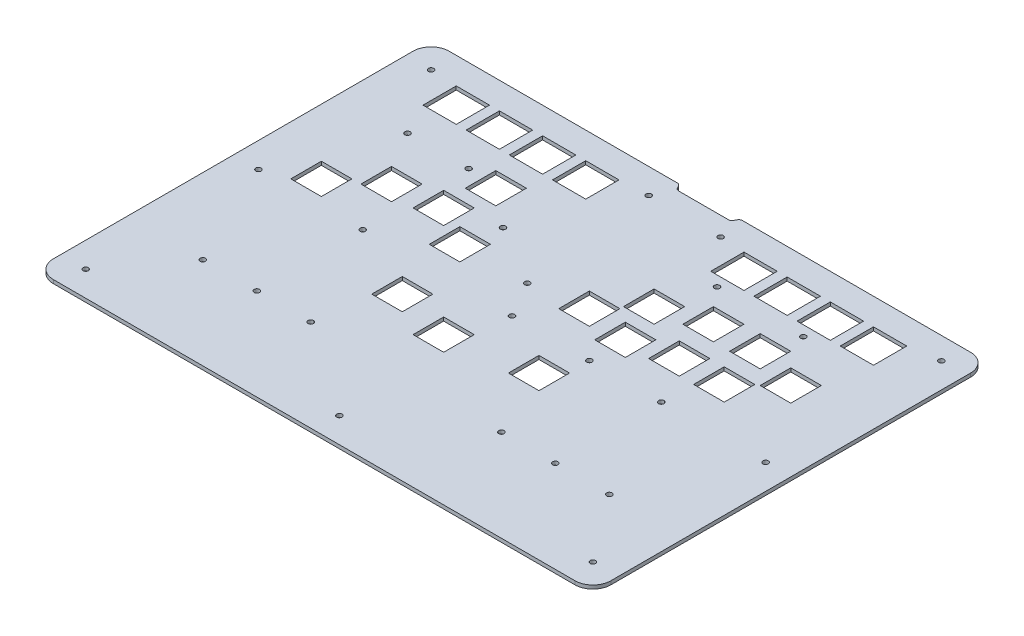
SolidWorks part; units mm, degrees
ref_plane "前视基准面" through (0, 0, 0) normal (0, 0, 1) x (1, 0, 0)
ref_plane "上视基准面" through (0, 0, 0) normal (0, 1, 0) x (1, 0, 0)
ref_plane "右视基准面" through (0, 0, 0) normal (1, 0, 0) x (0, 0, -1)
sketch "草图1" plane through (0, 0, 0) normal (0, 1, 0) x (1, 0, 0)
  line L0 (183.25, -128.5) -> (183.25, -131.5) construction
  line L1 (10, 0) -> (136.8844, 0)
  line L2 (0, -10) -> (0, -210)
  line L3 (10, -220) -> (300, -220)
  line L4 (310, -10) -> (310, -210)
  line L5 (28.75, -14.75) -> (47.25, -14.75)
  line L6 (28.75, -14.75) -> (28.75, -33.25)
  line L7 (28.75, -33.25) -> (47.25, -33.25)
  line L8 (173, -85) -> (173, 0) construction
  line L9 (173, -85) -> (310, -85) construction
  line L10 (190, -66) -> (190, 0) construction
  line L11 (215, -58) -> (215, 0) construction
  line L12 (241, -58) -> (241, 0) construction
  line L13 (247, -84) -> (247, 0) construction
  line L14 (222, -84) -> (222, 0) construction
  line L15 (0, -220) -> (310, 0) construction
  line L16 (241, -58) -> (310, -58) construction
  line L17 (247, -84) -> (310, -84) construction
  line L18 (215, -58) -> (310, -58) construction
  line L19 (222, -84) -> (310, -84) construction
  line L20 (190, -66) -> (310, -66) construction
  line L21 (310, -220) -> (0, 0) construction
  line L22 (141.1791, -3.5) -> (143.5, -3.5)
  line L23 (139.4291, -2.4682) -> (138.6344, -1.0318)
  line L24 (170.5709, -2.4682) -> (171.3656, -1.0318)
  line L25 (173.1156, 0) -> (300, 0)
  line L26 (155, -110) -> (155, -220) construction
  line L27 (47.25, -14.75) -> (47.25, -33.25)
  line L28 (28.75, -14.75) -> (47.25, -33.25) construction
  line L29 (28.75, -33.25) -> (47.25, -14.75) construction
  line L30 (52.75, -14.75) -> (71.25, -14.75)
  line L31 (52.75, -14.75) -> (52.75, -33.25)
  line L32 (52.75, -33.25) -> (71.25, -33.25)
  line L33 (71.25, -14.75) -> (71.25, -33.25)
  line L34 (52.75, -14.75) -> (71.25, -33.25) construction
  line L35 (52.75, -33.25) -> (71.25, -14.75) construction
  line L36 (76.75, -14.75) -> (95.25, -14.75)
  line L37 (76.75, -14.75) -> (76.75, -33.25)
  line L38 (76.75, -33.25) -> (95.25, -33.25)
  line L39 (95.25, -14.75) -> (95.25, -33.25)
  line L40 (76.75, -14.75) -> (95.25, -33.25) construction
  line L41 (76.75, -33.25) -> (95.25, -14.75) construction
  line L42 (100.75, -14.75) -> (119.25, -14.75)
  line L43 (100.75, -14.75) -> (100.75, -33.25)
  line L44 (100.75, -33.25) -> (119.25, -33.25)
  line L45 (119.25, -14.75) -> (119.25, -33.25)
  line L46 (100.75, -14.75) -> (119.25, -33.25) construction
  line L47 (100.75, -33.25) -> (119.25, -14.75) construction
  line L48 (188.75, -14.75) -> (207.25, -14.75)
  line L49 (188.75, -14.75) -> (188.75, -33.25)
  line L50 (188.75, -33.25) -> (207.25, -33.25)
  line L51 (207.25, -14.75) -> (207.25, -33.25)
  line L52 (188.75, -14.75) -> (207.25, -33.25) construction
  line L53 (188.75, -33.25) -> (207.25, -14.75) construction
  line L54 (212.75, -14.75) -> (231.25, -14.75)
  line L55 (212.75, -14.75) -> (212.75, -33.25)
  line L56 (212.75, -33.25) -> (231.25, -33.25)
  line L57 (231.25, -14.75) -> (231.25, -33.25)
  line L58 (212.75, -14.75) -> (231.25, -33.25) construction
  line L59 (212.75, -33.25) -> (231.25, -14.75) construction
  line L60 (236.75, -14.75) -> (255.25, -14.75)
  line L61 (236.75, -14.75) -> (236.75, -33.25)
  line L62 (236.75, -33.25) -> (255.25, -33.25)
  line L63 (255.25, -14.75) -> (255.25, -33.25)
  line L64 (236.75, -14.75) -> (255.25, -33.25) construction
  line L65 (236.75, -33.25) -> (255.25, -14.75) construction
  line L66 (260.75, -14.75) -> (279.25, -14.75)
  line L67 (260.75, -14.75) -> (260.75, -33.25)
  line L68 (260.75, -33.25) -> (279.25, -33.25)
  line L69 (279.25, -14.75) -> (279.25, -33.25)
  line L70 (260.75, -14.75) -> (279.25, -33.25) construction
  line L71 (260.75, -33.25) -> (279.25, -14.75) construction
  line L72 (183, -123) -> (197, -123) construction
  line L73 (183, -123) -> (183, -128.25) construction
  line L74 (183, -137) -> (197, -137) construction
  line L75 (197, -123) -> (197, -128.25) construction
  line L76 (183, -123) -> (197, -137) construction
  line L77 (183, -137) -> (197, -123) construction
  line L78 (183.25, -128.5) -> (183, -128.25) construction
  line L79 (183.25, -131.5) -> (183, -131.75) construction
  line L80 (196.75, -128.5) -> (196.75, -131.5) construction
  line L81 (196.75, -128.5) -> (197, -128.25) construction
  line L82 (196.75, -131.5) -> (197, -131.75) construction
  line L83 (183, -131.75) -> (183, -137) construction
  line L84 (197, -131.75) -> (197, -137) construction
  line L85 (31.25, -22.5) -> (31.25, -25.5) construction
  line L86 (31, -17) -> (45, -17) construction
  line L87 (31, -17) -> (31, -22.25) construction
  line L88 (31, -31) -> (45, -31) construction
  line L89 (45, -17) -> (45, -22.25) construction
  line L90 (31, -17) -> (45, -31) construction
  line L91 (31, -31) -> (45, -17) construction
  line L92 (31.25, -22.5) -> (31, -22.25) construction
  line L93 (31.25, -25.5) -> (31, -25.75) construction
  line L94 (44.75, -22.5) -> (44.75, -25.5) construction
  line L95 (44.75, -22.5) -> (45, -22.25) construction
  line L96 (44.75, -25.5) -> (45, -25.75) construction
  line L97 (31, -25.75) -> (31, -31) construction
  line L98 (45, -25.75) -> (45, -31) construction
  line L99 (55.25, -22.5) -> (55.25, -25.5) construction
  line L100 (55, -17) -> (69, -17) construction
  line L101 (55, -17) -> (55, -22.25) construction
  line L102 (55, -31) -> (69, -31) construction
  line L103 (69, -17) -> (69, -22.25) construction
  line L104 (55, -17) -> (69, -31) construction
  line L105 (55, -31) -> (69, -17) construction
  line L106 (55.25, -22.5) -> (55, -22.25) construction
  line L107 (55.25, -25.5) -> (55, -25.75) construction
  line L108 (68.75, -22.5) -> (68.75, -25.5) construction
  line L109 (68.75, -22.5) -> (69, -22.25) construction
  line L110 (68.75, -25.5) -> (69, -25.75) construction
  line L111 (55, -25.75) -> (55, -31) construction
  line L112 (69, -25.75) -> (69, -31) construction
  line L113 (79.25, -22.5) -> (79.25, -25.5) construction
  line L114 (79, -17) -> (93, -17) construction
  line L115 (79, -17) -> (79, -22.25) construction
  line L116 (79, -31) -> (93, -31) construction
  line L117 (93, -17) -> (93, -22.25) construction
  line L118 (79, -17) -> (93, -31) construction
  line L119 (79, -31) -> (93, -17) construction
  line L120 (79.25, -22.5) -> (79, -22.25) construction
  line L121 (79.25, -25.5) -> (79, -25.75) construction
  line L122 (92.75, -22.5) -> (92.75, -25.5) construction
  line L123 (92.75, -22.5) -> (93, -22.25) construction
  line L124 (92.75, -25.5) -> (93, -25.75) construction
  line L125 (79, -25.75) -> (79, -31) construction
  line L126 (93, -25.75) -> (93, -31) construction
  line L127 (103.25, -22.5) -> (103.25, -25.5) construction
  line L128 (103, -17) -> (117, -17) construction
  line L129 (103, -17) -> (103, -22.25) construction
  line L130 (103, -31) -> (117, -31) construction
  line L131 (117, -17) -> (117, -22.25) construction
  line L132 (103, -17) -> (117, -31) construction
  line L133 (103, -31) -> (117, -17) construction
  line L134 (103.25, -22.5) -> (103, -22.25) construction
  line L135 (103.25, -25.5) -> (103, -25.75) construction
  line L136 (116.75, -22.5) -> (116.75, -25.5) construction
  line L137 (116.75, -22.5) -> (117, -22.25) construction
  line L138 (116.75, -25.5) -> (117, -25.75) construction
  line L139 (103, -25.75) -> (103, -31) construction
  line L140 (117, -25.75) -> (117, -31) construction
  line L141 (191.25, -22.5) -> (191.25, -25.5) construction
  line L142 (191, -17) -> (205, -17) construction
  line L143 (191, -17) -> (191, -22.25) construction
  line L144 (191, -31) -> (205, -31) construction
  line L145 (205, -17) -> (205, -22.25) construction
  line L146 (191, -17) -> (205, -31) construction
  line L147 (191, -31) -> (205, -17) construction
  line L148 (191.25, -22.5) -> (191, -22.25) construction
  line L149 (191.25, -25.5) -> (191, -25.75) construction
  line L150 (204.75, -22.5) -> (204.75, -25.5) construction
  line L151 (204.75, -22.5) -> (205, -22.25) construction
  line L152 (204.75, -25.5) -> (205, -25.75) construction
  line L153 (191, -25.75) -> (191, -31) construction
  line L154 (205, -25.75) -> (205, -31) construction
  line L155 (215.25, -22.5) -> (215.25, -25.5) construction
  line L156 (215, -17) -> (229, -17) construction
  line L157 (215, -17) -> (215, -22.25) construction
  line L158 (215, -31) -> (229, -31) construction
  line L159 (229, -17) -> (229, -22.25) construction
  line L160 (215, -17) -> (229, -31) construction
  line L161 (215, -31) -> (229, -17) construction
  line L162 (215.25, -22.5) -> (215, -22.25) construction
  line L163 (215.25, -25.5) -> (215, -25.75) construction
  line L164 (228.75, -22.5) -> (228.75, -25.5) construction
  line L165 (228.75, -22.5) -> (229, -22.25) construction
  line L166 (228.75, -25.5) -> (229, -25.75) construction
  line L167 (215, -25.75) -> (215, -31) construction
  line L168 (229, -25.75) -> (229, -31) construction
  line L169 (239.25, -22.5) -> (239.25, -25.5) construction
  line L170 (239, -17) -> (253, -17) construction
  line L171 (239, -17) -> (239, -22.25) construction
  line L172 (239, -31) -> (253, -31) construction
  line L173 (253, -17) -> (253, -22.25) construction
  line L174 (239, -17) -> (253, -31) construction
  line L175 (239, -31) -> (253, -17) construction
  line L176 (239.25, -22.5) -> (239, -22.25) construction
  line L177 (239.25, -25.5) -> (239, -25.75) construction
  line L178 (252.75, -22.5) -> (252.75, -25.5) construction
  line L179 (252.75, -22.5) -> (253, -22.25) construction
  line L180 (252.75, -25.5) -> (253, -25.75) construction
  line L181 (239, -25.75) -> (239, -31) construction
  line L182 (253, -25.75) -> (253, -31) construction
  line L183 (263.25, -22.5) -> (263.25, -25.5) construction
  line L184 (263, -17) -> (277, -17) construction
  line L185 (263, -17) -> (263, -22.25) construction
  line L186 (263, -31) -> (277, -31) construction
  line L187 (277, -17) -> (277, -22.25) construction
  line L188 (263, -17) -> (277, -31) construction
  line L189 (263, -31) -> (277, -17) construction
  line L190 (263.25, -22.5) -> (263, -22.25) construction
  line L191 (263.25, -25.5) -> (263, -25.75) construction
  line L192 (276.75, -22.5) -> (276.75, -25.5) construction
  line L193 (276.75, -22.5) -> (277, -22.25) construction
  line L194 (276.75, -25.5) -> (277, -25.75) construction
  line L195 (263, -25.75) -> (263, -31) construction
  line L196 (277, -25.75) -> (277, -31) construction
  line L197 (259.25, -64.5) -> (259.25, -67.5) construction
  line L198 (259, -59) -> (273, -59) construction
  line L199 (259, -59) -> (259, -64.25) construction
  line L200 (259, -73) -> (273, -73) construction
  line L201 (273, -59) -> (273, -64.25) construction
  line L202 (259, -59) -> (273, -73) construction
  line L203 (259, -73) -> (273, -59) construction
  line L204 (259.25, -64.5) -> (259, -64.25) construction
  line L205 (259.25, -67.5) -> (259, -67.75) construction
  line L206 (272.75, -64.5) -> (272.75, -67.5) construction
  line L207 (272.75, -64.5) -> (273, -64.25) construction
  line L208 (272.75, -67.5) -> (273, -67.75) construction
  line L209 (259, -67.75) -> (259, -73) construction
  line L210 (273, -67.75) -> (273, -73) construction
  line L211 (240.25, -82.5) -> (240.25, -85.5) construction
  line L212 (240, -77) -> (254, -77) construction
  line L213 (240, -77) -> (240, -82.25) construction
  line L214 (240, -91) -> (254, -91) construction
  line L215 (254, -77) -> (254, -82.25) construction
  line L216 (240, -77) -> (254, -91) construction
  line L217 (240, -91) -> (254, -77) construction
  line L218 (240.25, -82.5) -> (240, -82.25) construction
  line L219 (240.25, -85.5) -> (240, -85.75) construction
  line L220 (253.75, -82.5) -> (253.75, -85.5) construction
  line L221 (253.75, -82.5) -> (254, -82.25) construction
  line L222 (253.75, -85.5) -> (254, -85.75) construction
  line L223 (240, -85.75) -> (240, -91) construction
  line L224 (254, -85.75) -> (254, -91) construction
  line L225 (234.25, -56.5) -> (234.25, -59.5) construction
  line L226 (234, -51) -> (248, -51) construction
  line L227 (234, -51) -> (234, -56.25) construction
  line L228 (234, -65) -> (248, -65) construction
  line L229 (248, -51) -> (248, -56.25) construction
  line L230 (234, -51) -> (248, -65) construction
  line L231 (234, -65) -> (248, -51) construction
  line L232 (234.25, -56.5) -> (234, -56.25) construction
  line L233 (234.25, -59.5) -> (234, -59.75) construction
  line L234 (247.75, -56.5) -> (247.75, -59.5) construction
  line L235 (247.75, -56.5) -> (248, -56.25) construction
  line L236 (247.75, -59.5) -> (248, -59.75) construction
  line L237 (234, -59.75) -> (234, -65) construction
  line L238 (248, -59.75) -> (248, -65) construction
  line L239 (215.25, -82.5) -> (215.25, -85.5) construction
  line L240 (215, -77) -> (229, -77) construction
  line L241 (215, -77) -> (215, -82.25) construction
  line L242 (215, -91) -> (229, -91) construction
  line L243 (229, -77) -> (229, -82.25) construction
  line L244 (215, -77) -> (229, -91) construction
  line L245 (215, -91) -> (229, -77) construction
  line L246 (215.25, -82.5) -> (215, -82.25) construction
  line L247 (215.25, -85.5) -> (215, -85.75) construction
  line L248 (228.75, -82.5) -> (228.75, -85.5) construction
  line L249 (228.75, -82.5) -> (229, -82.25) construction
  line L250 (228.75, -85.5) -> (229, -85.75) construction
  line L251 (215, -85.75) -> (215, -91) construction
  line L252 (229, -85.75) -> (229, -91) construction
  line L253 (29.25, -95.5) -> (29.25, -98.5) construction
  line L254 (29, -90) -> (43, -90) construction
  line L255 (29, -90) -> (29, -95.25) construction
  line L256 (29, -104) -> (43, -104) construction
  line L257 (43, -90) -> (43, -95.25) construction
  line L258 (29, -90) -> (43, -104) construction
  line L259 (29, -104) -> (43, -90) construction
  line L260 (29.25, -95.5) -> (29, -95.25) construction
  line L261 (29.25, -98.5) -> (29, -98.75) construction
  line L262 (42.75, -95.5) -> (42.75, -98.5) construction
  line L263 (42.75, -95.5) -> (43, -95.25) construction
  line L264 (42.75, -98.5) -> (43, -98.75) construction
  line L265 (29, -98.75) -> (29, -104) construction
  line L266 (43, -98.75) -> (43, -104) construction
  line L267 (51.25, -78.5) -> (51.25, -81.5) construction
  line L268 (51, -73) -> (65, -73) construction
  line L269 (51, -73) -> (51, -78.25) construction
  line L270 (51, -87) -> (65, -87) construction
  line L271 (65, -73) -> (65, -78.25) construction
  line L272 (51, -73) -> (65, -87) construction
  line L273 (51, -87) -> (65, -73) construction
  line L274 (51.25, -78.5) -> (51, -78.25) construction
  line L275 (51.25, -81.5) -> (51, -81.75) construction
  line L276 (64.75, -78.5) -> (64.75, -81.5) construction
  line L277 (64.75, -78.5) -> (65, -78.25) construction
  line L278 (64.75, -81.5) -> (65, -81.75) construction
  line L279 (51, -81.75) -> (51, -87) construction
  line L280 (65, -81.75) -> (65, -87) construction
  line L281 (77.25, -75.5) -> (77.25, -78.5) construction
  line L282 (77, -70) -> (91, -70) construction
  line L283 (77, -70) -> (77, -75.25) construction
  line L284 (77, -84) -> (91, -84) construction
  line L285 (91, -70) -> (91, -75.25) construction
  line L286 (77, -70) -> (91, -84) construction
  line L287 (77, -84) -> (91, -70) construction
  line L288 (77.25, -75.5) -> (77, -75.25) construction
  line L289 (77.25, -78.5) -> (77, -78.75) construction
  line L290 (90.75, -75.5) -> (90.75, -78.5) construction
  line L291 (90.75, -75.5) -> (91, -75.25) construction
  line L292 (90.75, -78.5) -> (91, -78.75) construction
  line L293 (77, -78.75) -> (77, -84) construction
  line L294 (91, -78.75) -> (91, -84) construction
  line L295 (82.25, -51.5) -> (82.25, -54.5) construction
  line L296 (82, -46) -> (96, -46) construction
  line L297 (82, -46) -> (82, -51.25) construction
  line L298 (82, -60) -> (96, -60) construction
  line L299 (96, -46) -> (96, -51.25) construction
  line L300 (82, -46) -> (96, -60) construction
  line L301 (82, -60) -> (96, -46) construction
  line L302 (82.25, -51.5) -> (82, -51.25) construction
  line L303 (82.25, -54.5) -> (82, -54.75) construction
  line L304 (95.75, -51.5) -> (95.75, -54.5) construction
  line L305 (95.75, -51.5) -> (96, -51.25) construction
  line L306 (95.75, -54.5) -> (96, -54.75) construction
  line L307 (82, -54.75) -> (82, -60) construction
  line L308 (96, -54.75) -> (96, -60) construction
  line L309 (99.25, -88.5) -> (99.25, -91.5) construction
  line L310 (99, -83) -> (113, -83) construction
  line L311 (99, -83) -> (99, -88.25) construction
  line L312 (99, -97) -> (113, -97) construction
  line L313 (113, -83) -> (113, -88.25) construction
  line L314 (99, -83) -> (113, -97) construction
  line L315 (99, -97) -> (113, -83) construction
  line L316 (99.25, -88.5) -> (99, -88.25) construction
  line L317 (99.25, -91.5) -> (99, -91.75) construction
  line L318 (112.75, -88.5) -> (112.75, -91.5) construction
  line L319 (112.75, -88.5) -> (113, -88.25) construction
  line L320 (112.75, -91.5) -> (113, -91.75) construction
  line L321 (99, -91.75) -> (99, -97) construction
  line L322 (113, -91.75) -> (113, -97) construction
  line L323 (208.25, -56.5) -> (208.25, -59.5) construction
  line L324 (208, -51) -> (222, -51) construction
  line L325 (208, -51) -> (208, -56.25) construction
  line L326 (208, -65) -> (222, -65) construction
  line L327 (222, -51) -> (222, -56.25) construction
  line L328 (208, -51) -> (222, -65) construction
  line L329 (208, -65) -> (222, -51) construction
  line L330 (208.25, -56.5) -> (208, -56.25) construction
  line L331 (208.25, -59.5) -> (208, -59.75) construction
  line L332 (221.75, -56.5) -> (221.75, -59.5) construction
  line L333 (221.75, -56.5) -> (222, -56.25) construction
  line L334 (221.75, -59.5) -> (222, -59.75) construction
  line L335 (208, -59.75) -> (208, -65) construction
  line L336 (222, -59.75) -> (222, -65) construction
  line L337 (183.25, -64.5) -> (183.25, -67.5) construction
  line L338 (183, -59) -> (197, -59) construction
  line L339 (183, -59) -> (183, -64.25) construction
  line L340 (183, -73) -> (197, -73) construction
  line L341 (197, -59) -> (197, -64.25) construction
  line L342 (183, -59) -> (197, -73) construction
  line L343 (183, -73) -> (197, -59) construction
  line L344 (183.25, -64.5) -> (183, -64.25) construction
  line L345 (183.25, -67.5) -> (183, -67.75) construction
  line L346 (196.75, -64.5) -> (196.75, -67.5) construction
  line L347 (196.75, -64.5) -> (197, -64.25) construction
  line L348 (196.75, -67.5) -> (197, -67.75) construction
  line L349 (183, -67.75) -> (183, -73) construction
  line L350 (197, -67.75) -> (197, -73) construction
  line L351 (191.25, -88.5) -> (191.25, -91.5) construction
  line L352 (191, -83) -> (205, -83) construction
  line L353 (191, -83) -> (191, -88.25) construction
  line L354 (191, -97) -> (205, -97) construction
  line L355 (205, -83) -> (205, -88.25) construction
  line L356 (191, -83) -> (205, -97) construction
  line L357 (191, -97) -> (205, -83) construction
  line L358 (191.25, -88.5) -> (191, -88.25) construction
  line L359 (191.25, -91.5) -> (191, -91.75) construction
  line L360 (204.75, -88.5) -> (204.75, -91.5) construction
  line L361 (204.75, -88.5) -> (205, -88.25) construction
  line L362 (204.75, -91.5) -> (205, -91.75) construction
  line L363 (191, -91.75) -> (191, -97) construction
  line L364 (205, -91.75) -> (205, -97) construction
  line L365 (166.25, -83.5) -> (166.25, -86.5) construction
  line L366 (166, -78) -> (180, -78) construction
  line L367 (166, -78) -> (166, -83.25) construction
  line L368 (166, -92) -> (180, -92) construction
  line L369 (180, -78) -> (180, -83.25) construction
  line L370 (166, -78) -> (180, -92) construction
  line L371 (166, -92) -> (180, -78) construction
  line L372 (166.25, -83.5) -> (166, -83.25) construction
  line L373 (166.25, -86.5) -> (166, -86.75) construction
  line L374 (179.75, -83.5) -> (179.75, -86.5) construction
  line L375 (179.75, -83.5) -> (180, -83.25) construction
  line L376 (179.75, -86.5) -> (180, -86.75) construction
  line L377 (166, -86.75) -> (166, -92) construction
  line L378 (180, -86.75) -> (180, -92) construction
  line L379 (107.25, -128.5) -> (107.25, -131.5) construction
  line L380 (107, -123) -> (121, -123) construction
  line L381 (107, -123) -> (107, -128.25) construction
  line L382 (107, -137) -> (121, -137) construction
  line L383 (121, -123) -> (121, -128.25) construction
  line L384 (107, -123) -> (121, -137) construction
  line L385 (107, -137) -> (121, -123) construction
  line L386 (107.25, -128.5) -> (107, -128.25) construction
  line L387 (107.25, -131.5) -> (107, -131.75) construction
  line L388 (120.75, -128.5) -> (120.75, -131.5) construction
  line L389 (120.75, -128.5) -> (121, -128.25) construction
  line L390 (120.75, -131.5) -> (121, -131.75) construction
  line L391 (107, -131.75) -> (107, -137) construction
  line L392 (121, -131.75) -> (121, -137) construction
  line L393 (138.25, -136.5) -> (138.25, -139.5) construction
  line L394 (138, -131) -> (152, -131) construction
  line L395 (138, -131) -> (138, -136.25) construction
  line L396 (138, -145) -> (152, -145) construction
  line L397 (152, -131) -> (152, -136.25) construction
  line L398 (138, -131) -> (152, -145) construction
  line L399 (138, -145) -> (152, -131) construction
  line L400 (138.25, -136.5) -> (138, -136.25) construction
  line L401 (138.25, -139.5) -> (138, -139.75) construction
  line L402 (151.75, -136.5) -> (151.75, -139.5) construction
  line L403 (151.75, -136.5) -> (152, -136.25) construction
  line L404 (151.75, -139.5) -> (152, -139.75) construction
  line L405 (138, -139.75) -> (138, -145) construction
  line L406 (152, -139.75) -> (152, -145) construction
  line L407 (166.5, -3.5) -> (168.8209, -3.5)
  line L409 (143.5, -3.5) -> (143.5, -55.5) construction
  line L410 (143.5, -55.5) -> (166.5, -55.5) construction
  line L411 (166.5, -3.5) -> (166.5, -55.5) construction
  line L412 (143.5, -3.5) -> (166.5, -55.5) construction
  line L413 (143.5, -55.5) -> (166.5, -3.5) construction
  line L414 (143.5, -3.5) -> (166.5, -3.5)
  line L415 (80.5, -44.5) -> (97.5, -44.5)
  line L422 (80.5, -44.5) -> (80.5, -61.5)
  line L423 (80.5, -61.5) -> (97.5, -61.5)
  line L424 (97.5, -44.5) -> (97.5, -61.5)
  line L425 (80.5, -44.5) -> (97.5, -61.5) construction
  line L426 (80.5, -61.5) -> (97.5, -44.5) construction
  line L427 (75.5, -68.5) -> (92.5, -68.5)
  line L428 (75.5, -68.5) -> (75.5, -85.5)
  line L429 (75.5, -85.5) -> (92.5, -85.5)
  line L430 (92.5, -68.5) -> (92.5, -85.5)
  line L431 (75.5, -68.5) -> (92.5, -85.5) construction
  line L432 (75.5, -85.5) -> (92.5, -68.5) construction
  line L433 (97.5, -81.5) -> (114.5, -81.5)
  line L434 (97.5, -81.5) -> (97.5, -98.5)
  line L435 (97.5, -98.5) -> (114.5, -98.5)
  line L436 (114.5, -81.5) -> (114.5, -98.5)
  line L437 (97.5, -81.5) -> (114.5, -98.5) construction
  line L438 (97.5, -98.5) -> (114.5, -81.5) construction
  line L439 (49.5, -71.5) -> (66.5, -71.5)
  line L440 (49.5, -71.5) -> (49.5, -88.5)
  line L441 (49.5, -88.5) -> (66.5, -88.5)
  line L442 (66.5, -71.5) -> (66.5, -88.5)
  line L443 (49.5, -71.5) -> (66.5, -88.5) construction
  line L444 (49.5, -88.5) -> (66.5, -71.5) construction
  line L445 (27.5, -88.5) -> (44.5, -88.5)
  line L446 (27.5, -88.5) -> (27.5, -105.5)
  line L447 (27.5, -105.5) -> (44.5, -105.5)
  line L448 (44.5, -88.5) -> (44.5, -105.5)
  line L449 (27.5, -88.5) -> (44.5, -105.5) construction
  line L450 (27.5, -105.5) -> (44.5, -88.5) construction
  line L451 (105.5, -121.5) -> (122.5, -121.5)
  line L452 (105.5, -121.5) -> (105.5, -138.5)
  line L453 (105.5, -138.5) -> (122.5, -138.5)
  line L454 (122.5, -121.5) -> (122.5, -138.5)
  line L455 (105.5, -121.5) -> (122.5, -138.5) construction
  line L456 (105.5, -138.5) -> (122.5, -121.5) construction
  line L457 (136.5, -129.5) -> (153.5, -129.5)
  line L458 (136.5, -129.5) -> (136.5, -146.5)
  line L459 (136.5, -146.5) -> (153.5, -146.5)
  line L460 (153.5, -129.5) -> (153.5, -146.5)
  line L461 (136.5, -129.5) -> (153.5, -146.5) construction
  line L462 (136.5, -146.5) -> (153.5, -129.5) construction
  line L463 (181.5, -121.5) -> (198.5, -121.5)
  line L464 (181.5, -121.5) -> (181.5, -138.5)
  line L465 (181.5, -138.5) -> (198.5, -138.5)
  line L466 (198.5, -121.5) -> (198.5, -138.5)
  line L467 (181.5, -121.5) -> (198.5, -138.5) construction
  line L468 (181.5, -138.5) -> (198.5, -121.5) construction
  line L469 (164.5, -76.5) -> (181.5, -76.5)
  line L470 (164.5, -76.5) -> (164.5, -93.5)
  line L471 (164.5, -93.5) -> (181.5, -93.5)
  line L472 (181.5, -76.5) -> (181.5, -93.5)
  line L473 (164.5, -76.5) -> (181.5, -93.5) construction
  line L474 (164.5, -93.5) -> (181.5, -76.5) construction
  line L475 (181.5, -57.5) -> (198.5, -57.5)
  line L476 (181.5, -57.5) -> (181.5, -74.5)
  line L477 (181.5, -74.5) -> (198.5, -74.5)
  line L478 (198.5, -57.5) -> (198.5, -74.5)
  line L479 (181.5, -57.5) -> (198.5, -74.5) construction
  line L480 (181.5, -74.5) -> (198.5, -57.5) construction
  line L481 (189.5, -81.5) -> (206.5, -81.5)
  line L482 (189.5, -81.5) -> (189.5, -98.5)
  line L483 (189.5, -98.5) -> (206.5, -98.5)
  line L484 (206.5, -81.5) -> (206.5, -98.5)
  line L485 (189.5, -81.5) -> (206.5, -98.5) construction
  line L486 (189.5, -98.5) -> (206.5, -81.5) construction
  line L487 (206.5, -49.5) -> (223.5, -49.5)
  line L488 (206.5, -49.5) -> (206.5, -66.5)
  line L489 (206.5, -66.5) -> (223.5, -66.5)
  line L490 (223.5, -49.5) -> (223.5, -66.5)
  line L491 (206.5, -49.5) -> (223.5, -66.5) construction
  line L492 (206.5, -66.5) -> (223.5, -49.5) construction
  line L493 (213.5, -75.5) -> (230.5, -75.5)
  line L494 (213.5, -75.5) -> (213.5, -92.5)
  line L495 (213.5, -92.5) -> (230.5, -92.5)
  line L496 (230.5, -75.5) -> (230.5, -92.5)
  line L497 (213.5, -75.5) -> (230.5, -92.5) construction
  line L498 (213.5, -92.5) -> (230.5, -75.5) construction
  line L499 (232.5, -49.5) -> (249.5, -49.5)
  line L500 (232.5, -49.5) -> (232.5, -66.5)
  line L501 (232.5, -66.5) -> (249.5, -66.5)
  line L502 (249.5, -49.5) -> (249.5, -66.5)
  line L503 (232.5, -49.5) -> (249.5, -66.5) construction
  line L504 (232.5, -66.5) -> (249.5, -49.5) construction
  line L505 (238.5, -75.5) -> (255.5, -75.5)
  line L506 (238.5, -75.5) -> (238.5, -92.5)
  line L507 (238.5, -92.5) -> (255.5, -92.5)
  line L508 (255.5, -75.5) -> (255.5, -92.5)
  line L509 (238.5, -75.5) -> (255.5, -92.5) construction
  line L510 (238.5, -92.5) -> (255.5, -75.5) construction
  line L511 (257.5, -57.5) -> (274.5, -57.5)
  line L512 (257.5, -57.5) -> (257.5, -74.5)
  line L513 (257.5, -74.5) -> (274.5, -74.5)
  line L514 (274.5, -57.5) -> (274.5, -74.5)
  line L515 (257.5, -57.5) -> (274.5, -74.5) construction
  line L516 (257.5, -74.5) -> (274.5, -57.5) construction
  arc A0 (10, 0) -> (0, -10) centre (10, -10) ccw
  arc A1 (0, -210) -> (10, -220) centre (10, -210) ccw
  arc A2 (300, -220) -> (310, -210) centre (300, -210) ccw
  arc A3 (300, 0) -> (310, -10) centre (300, -10) cw
  circle A8 centre (173, -85) radius 11 construction
  circle A9 centre (190, -66) radius 11 construction
  circle A11 centre (215, -58) radius 11 construction
  circle A12 centre (222, -84) radius 11 construction
  circle A13 centre (247, -84) radius 11 construction
  circle A14 centre (241, -58) radius 11 construction
  circle A15 centre (14, -14) radius 1.5
  circle A16 centre (14, -206) radius 1.5
  circle A17 centre (296, -206) radius 1.5
  circle A18 centre (296, -12.2857) radius 1.5
  arc A19 (173.1156, 0) -> (171.3656, -1.0318) centre (173.1156, -2) ccw
  arc A20 (170.5709, -2.4682) -> (168.8209, -3.5) centre (168.8209, -1.5) cw
  arc A21 (141.1791, -3.5) -> (139.4291, -2.4682) centre (141.1791, -1.5) cw
  arc A22 (136.8844, 0) -> (138.6344, -1.0318) centre (136.8844, -2) cw
  circle A24 centre (198, -90) radius 11 construction
  circle A25 centre (114, -130) radius 13.5 construction
  circle A26 centre (190, -130) radius 13.5 construction
  circle A27 centre (155, -206) radius 1.5
  circle A28 centre (175, -14) radius 1.5
  circle A29 centre (145, -138) radius 11 construction
  circle A30 centre (106, -90) radius 11 construction
  circle A31 centre (84, -77) radius 11 construction
  circle A32 centre (58, -80) radius 11 construction
  circle A33 centre (36, -97) radius 11 construction
  circle A34 centre (89, -53) radius 11 construction
  circle A35 centre (266, -66) radius 11 construction
  circle A36 centre (110, -24) radius 4.5 construction
  circle A37 centre (86, -24) radius 4.5 construction
  circle A38 centre (62, -24) radius 4.5 construction
  circle A39 centre (38, -24) radius 4.5 construction
  circle A40 centre (198, -24) radius 4.5 construction
  circle A41 centre (222, -24) radius 4.5 construction
  circle A42 centre (246, -24) radius 4.5 construction
  circle A43 centre (270, -24) radius 4.5 construction
  circle A48 centre (135, -14) radius 1.5
  circle A51 centre (296, -110) radius 1.5
  circle A52 centre (14, -110) radius 1.5
  circle A53 centre (155, -110) radius 1.5
  circle A54 centre (72, -110) radius 1.5
  circle A55 centre (72, -168.9032) radius 1.5
  circle A56 centre (72, -51.0968) radius 1.5
  circle A57 centre (42, -168.9032) radius 1.5
  circle A58 centre (102, -168.9032) radius 1.5
  circle A59 centre (238, -110) radius 1.5
  circle A60 centre (238, -168.9032) radius 1.5
  circle A61 centre (268, -168.9032) radius 1.5
  circle A62 centre (208, -168.9032) radius 1.5
  circle A63 centre (246, -39) radius 1.5
  circle A64 centre (198, -39) radius 1.5
  circle A65 centre (110, -70) radius 1.5
  circle A66 centre (38, -51.0968) radius 1.5
  circle A67 centre (198, -110) radius 1.5
  circle A68 centre (143.5, -90) radius 1.5
  point P8 (0, 0)
  point P12 (0, -220)
  point P15 (310, -220)
  point P18 (310, 0)
  point P70 (171.9365, 0)
  point P73 (170, -3.5)
  point P76 (140, -3.5)
  point P79 (138.0635, 0)
  point P147 (190, -130)
  point P152 (155, -29.5)
  point P155 (183.25, -130)
  point P160 (196.75, -130)
  point P163 (38, -24)
  point P170 (31.25, -24)
  point P175 (44.75, -24)
  point P180 (62, -24)
  point P187 (55.25, -24)
  point P192 (68.75, -24)
  point P196 (86, -24)
  point P203 (79.25, -24)
  point P208 (92.75, -24)
  point P213 (110, -24)
  point P220 (103.25, -24)
  point P225 (116.75, -24)
  point P229 (198, -24)
  point P236 (191.25, -24)
  point P241 (204.75, -24)
  point P245 (222, -24)
  point P252 (215.25, -24)
  point P257 (228.75, -24)
  point P261 (246, -24)
  point P268 (239.25, -24)
  point P273 (252.75, -24)
  point P276 (89, -53)
  point P277 (270, -24)
  point P284 (263.25, -24)
  point P289 (276.75, -24)
  point P293 (266, -66)
  point P300 (259.25, -66)
  point P305 (272.75, -66)
  point P310 (247, -84)
  point P317 (240.25, -84)
  point P322 (253.75, -84)
  point P326 (241, -58)
  point P333 (234.25, -58)
  point P338 (247.75, -58)
  point P342 (222, -84)
  point P349 (215.25, -84)
  point P354 (228.75, -84)
  point P358 (36, -97)
  point P365 (29.25, -97)
  point P370 (42.75, -97)
  point P374 (58, -80)
  point P381 (51.25, -80)
  point P386 (64.75, -80)
  point P390 (84, -77)
  point P397 (77.25, -77)
  point P402 (90.75, -77)
  point P407 (89, -53)
  point P414 (82.25, -53)
  point P419 (95.75, -53)
  point P423 (106, -90)
  point P430 (99.25, -90)
  point P435 (112.75, -90)
  point P439 (215, -58)
  point P446 (208.25, -58)
  point P451 (221.75, -58)
  point P455 (190, -66)
  point P462 (183.25, -66)
  point P467 (196.75, -66)
  point P471 (198, -90)
  point P478 (191.25, -90)
  point P483 (204.75, -90)
  point P486 (84, -77)
  point P492 (173, -85)
  point P499 (166.25, -85)
  point P504 (179.75, -85)
  point P508 (114, -130)
  point P515 (107.25, -130)
  point P520 (120.75, -130)
  point P524 (145, -138)
  point P531 (138.25, -138)
  point P536 (151.75, -138)
  point P541 (106, -90)
  point P551 (58, -80)
  point P563 (36, -97)
  point P573 (114, -130)
  point P582 (145, -138)
  point P590 (190, -130)
  point P596 (173, -85)
  point P602 (190, -66)
  point P608 (198, -90)
  point P614 (215, -58)
  point P620 (222, -84)
  point P626 (241, -58)
  point P632 (247, -84)
  point P638 (266, -66)
  dimension "D3" = 10
  dimension "D7" = 90
  dimension "D10" = 22
  dimension "D15" = 53
  dimension "D16" = 22
  dimension "D19" = 22
  dimension "D20" = 22
  dimension "D21" = 22
  dimension "D22" = 84
  dimension "D23" = 22
  dimension "D24" = 22
  dimension "D32" = 22
  dimension "D34" = 3
  dimension "D37" = 3
  dimension "D40" = 3
  dimension "D43" = 3
  dimension "D47" = 3.5
  dimension "D50" = 140
  dimension "D51" = 2
  dimension "D52" = 90
  dimension "D54" = 27
  dimension "D56" = 27
  dimension "D59" = 3
  dimension "D61" = 14
  dimension "D62" = 3
  dimension "D64" = 22
  dimension "D8" = 22
  dimension "D9" = 22
  dimension "D11" = 22
  dimension "D12" = 22
  dimension "D13" = 22
  dimension "D76" = 9
  dimension "D84" = 9
  dimension "D86" = 3
  dimension "D89" = 18.5
  dimension "D92" = 18.5
  dimension "D95" = 18.5
  dimension "D98" = 3
  dimension "D101" = 18.5
  dimension "D103" = 18.5
  dimension "D87" = 3
  dimension "D301" = 3
  dimension "D302" = 3
  dimension "D304" = 3
  dimension "D305" = 3
  dimension "D306" = 3
  dimension "D308" = 3
  dimension "D310" = 3
  dimension "D312" = 3
  dimension "D313" = 3
  dimension "D314" = 3
  dimension "D317" = 3
  dimension "D319" = 3
  dimension "D321" = 3
  dimension "D323" = 3
  dimension "D324" = 3
  dimension "D325" = 3
  dimension "D1" = 220
  dimension "D2" = 310
  dimension "D14" = 89
  dimension "D17" = 85
  dimension "D18" = 137
  dimension "D25" = 66
  dimension "D26" = 120
  dimension "D27" = 36
  dimension "D28" = 58
  dimension "D29" = 95
  dimension "D30" = 88
  dimension "D31" = 69
  dimension "D33" = 63
  dimension "D35" = 14
  dimension "D36" = 14
  dimension "D38" = 14
  dimension "D39" = 14
  dimension "D41" = 14
  dimension "D42" = 14
  dimension "D44" = 14
  dimension "D45" = 12.2857
  dimension "D46" = 4
  dimension "D48" = 30
  dimension "D49" = 4
  dimension "D53" = 112
  dimension "D55" = 114
  dimension "D57" = 90
  dimension "D58" = 120
  dimension "D60" = 14
  dimension "D63" = 135
  dimension "D65" = 82
  dimension "D66" = 145
  dimension "D67" = 97
  dimension "D68" = 80
  dimension "D69" = 58
  dimension "D70" = 84
  dimension "D71" = 77
  dimension "D72" = 90
  dimension "D73" = 106
  dimension "D74" = 44
  dimension "D75" = 66
  dimension "D78" = 24
  dimension "D79" = 110
  dimension "D80" = 24
  dimension "D82" = 24
  dimension "D83" = 24
  dimension "D85" = 40
  dimension "D88" = 18.5
  dimension "D90" = 18.5
  dimension "D91" = 18.5
  dimension "D93" = 18.5
  dimension "D94" = 18.5
  dimension "D96" = 18.5
  dimension "D97" = 18.5
  dimension "D99" = 14
  dimension "D100" = 135
  dimension "D102" = 18.5
  dimension "D104" = 18.5
  dimension "D105" = 18.5
  dimension "D106" = 18.5
  dimension "D107" = 14
  dimension "D108" = 14
  dimension "D109" = 0.25
  dimension "D110" = 3
  dimension "D111" = 135
  dimension "D112" = 3
  dimension "D113" = 0.25
  dimension "D114" = 135
  dimension "D115" = 14
  dimension "D116" = 14
  dimension "D117" = 0.25
  dimension "D118" = 3
  dimension "D119" = 135
  dimension "D120" = 3
  dimension "D121" = 0.25
  dimension "D122" = 135
  dimension "D123" = 14
  dimension "D124" = 14
  dimension "D125" = 0.25
  dimension "D126" = 3
  dimension "D127" = 135
  dimension "D128" = 3
  dimension "D129" = 0.25
  dimension "D130" = 135
  dimension "D131" = 14
  dimension "D132" = 14
  dimension "D133" = 0.25
  dimension "D134" = 3
  dimension "D135" = 135
  dimension "D136" = 3
  dimension "D137" = 0.25
  dimension "D138" = 135
  dimension "D139" = 14
  dimension "D140" = 14
  dimension "D141" = 0.25
  dimension "D142" = 3
  dimension "D143" = 135
  dimension "D144" = 3
  dimension "D145" = 0.25
  dimension "D146" = 135
  dimension "D147" = 14
  dimension "D148" = 14
  dimension "D149" = 0.25
  dimension "D150" = 3
  dimension "D151" = 135
  dimension "D152" = 3
  dimension "D153" = 0.25
  dimension "D154" = 135
  dimension "D155" = 14
  dimension "D156" = 14
  dimension "D157" = 0.25
  dimension "D158" = 3
  dimension "D159" = 135
  dimension "D160" = 3
  dimension "D161" = 0.25
  dimension "D162" = 135
  dimension "D163" = 14
  dimension "D164" = 14
  dimension "D165" = 0.25
  dimension "D166" = 3
  dimension "D167" = 135
  dimension "D168" = 3
  dimension "D169" = 0.25
  dimension "D170" = 135
  dimension "D171" = 14
  dimension "D172" = 14
  dimension "D173" = 0.25
  dimension "D174" = 3
  dimension "D175" = 135
  dimension "D176" = 3
  dimension "D177" = 0.25
  dimension "D178" = 135
  dimension "D179" = 14
  dimension "D180" = 14
  dimension "D181" = 0.25
  dimension "D182" = 3
  dimension "D183" = 135
  dimension "D184" = 3
  dimension "D185" = 0.25
  dimension "D186" = 135
  dimension "D187" = 14
  dimension "D188" = 14
  dimension "D189" = 0.25
  dimension "D190" = 3
  dimension "D191" = 135
  dimension "D192" = 3
  dimension "D193" = 0.25
  dimension "D194" = 135
  dimension "D195" = 14
  dimension "D196" = 14
  dimension "D197" = 0.25
  dimension "D198" = 3
  dimension "D199" = 135
  dimension "D200" = 3
  dimension "D201" = 0.25
  dimension "D202" = 135
  dimension "D203" = 14
  dimension "D204" = 14
  dimension "D205" = 0.25
  dimension "D206" = 3
  dimension "D207" = 135
  dimension "D208" = 3
  dimension "D209" = 0.25
  dimension "D210" = 135
  dimension "D211" = 14
  dimension "D212" = 14
  dimension "D213" = 0.25
  dimension "D214" = 3
  dimension "D215" = 135
  dimension "D216" = 3
  dimension "D217" = 0.25
  dimension "D218" = 135
  dimension "D219" = 14
  dimension "D220" = 14
  dimension "D221" = 0.25
  dimension "D222" = 3
  dimension "D223" = 135
  dimension "D224" = 3
  dimension "D225" = 0.25
  dimension "D226" = 135
  dimension "D227" = 14
  dimension "D228" = 14
  dimension "D229" = 0.25
  dimension "D230" = 3
  dimension "D231" = 135
  dimension "D232" = 3
  dimension "D233" = 0.25
  dimension "D234" = 135
  dimension "D235" = 14
  dimension "D236" = 14
  dimension "D237" = 0.25
  dimension "D238" = 3
  dimension "D239" = 135
  dimension "D240" = 3
  dimension "D241" = 0.25
  dimension "D242" = 135
  dimension "D243" = 14
  dimension "D244" = 14
  dimension "D245" = 0.25
  dimension "D246" = 3
  dimension "D247" = 135
  dimension "D248" = 3
  dimension "D249" = 0.25
  dimension "D250" = 135
  dimension "D251" = 14
  dimension "D252" = 14
  dimension "D253" = 0.25
  dimension "D254" = 3
  dimension "D255" = 135
  dimension "D256" = 3
  dimension "D257" = 0.25
  dimension "D258" = 135
  dimension "D259" = 14
  dimension "D260" = 14
  dimension "D261" = 0.25
  dimension "D262" = 3
  dimension "D263" = 135
  dimension "D264" = 3
  dimension "D265" = 0.25
  dimension "D266" = 135
  dimension "D267" = 14
  dimension "D268" = 14
  dimension "D269" = 0.25
  dimension "D270" = 3
  dimension "D271" = 135
  dimension "D272" = 3
  dimension "D273" = 0.25
  dimension "D274" = 135
  dimension "D275" = 14
  dimension "D276" = 14
  dimension "D277" = 0.25
  dimension "D278" = 3
  dimension "D279" = 135
  dimension "D280" = 3
  dimension "D281" = 0.25
  dimension "D282" = 135
  dimension "D283" = 14
  dimension "D284" = 14
  dimension "D285" = 0.25
  dimension "D286" = 3
  dimension "D287" = 135
  dimension "D288" = 3
  dimension "D289" = 0.25
  dimension "D290" = 135
  dimension "D291" = 14
  dimension "D292" = 14
  dimension "D293" = 0.25
  dimension "D294" = 3
  dimension "D295" = 135
  dimension "D296" = 3
  dimension "D297" = 0.25
  dimension "D298" = 135
  dimension "D299" = 23
  dimension "D300" = 52
  dimension "D303" = 72
  dimension "D307" = 30
  dimension "D309" = 30
  dimension "D311" = 72
  dimension "D315" = 30
  dimension "D316" = 30
  dimension "D318" = 15
  dimension "D320" = 15
  dimension "D322" = 46
  dimension "D328" = 17
  dimension "D329" = 17
  dimension "D330" = 17
  dimension "D331" = 17
  dimension "D332" = 17
  dimension "D333" = 17
  dimension "D334" = 17
  dimension "D335" = 17
  dimension "D336" = 17
  dimension "D337" = 17
  dimension "D338" = 17
  dimension "D339" = 17
  dimension "D340" = 17
  dimension "D341" = 17
  dimension "D342" = 17
  dimension "D343" = 17
  dimension "D344" = 17
  dimension "D345" = 17
  dimension "D346" = 17
  dimension "D347" = 17
  dimension "D348" = 17
  dimension "D349" = 17
  dimension "D350" = 17
  dimension "D351" = 17
  dimension "D352" = 17
  dimension "D353" = 17
  dimension "D354" = 17
  dimension "D355" = 17
  dimension "D356" = 17
  dimension "D357" = 17
  dimension "D358" = 17
  dimension "D359" = 17
  dimension "D77" = 4
  dimension "D81" = 4
extrude "凸台-拉伸1" add sketch "草图1" along normal blind 2
